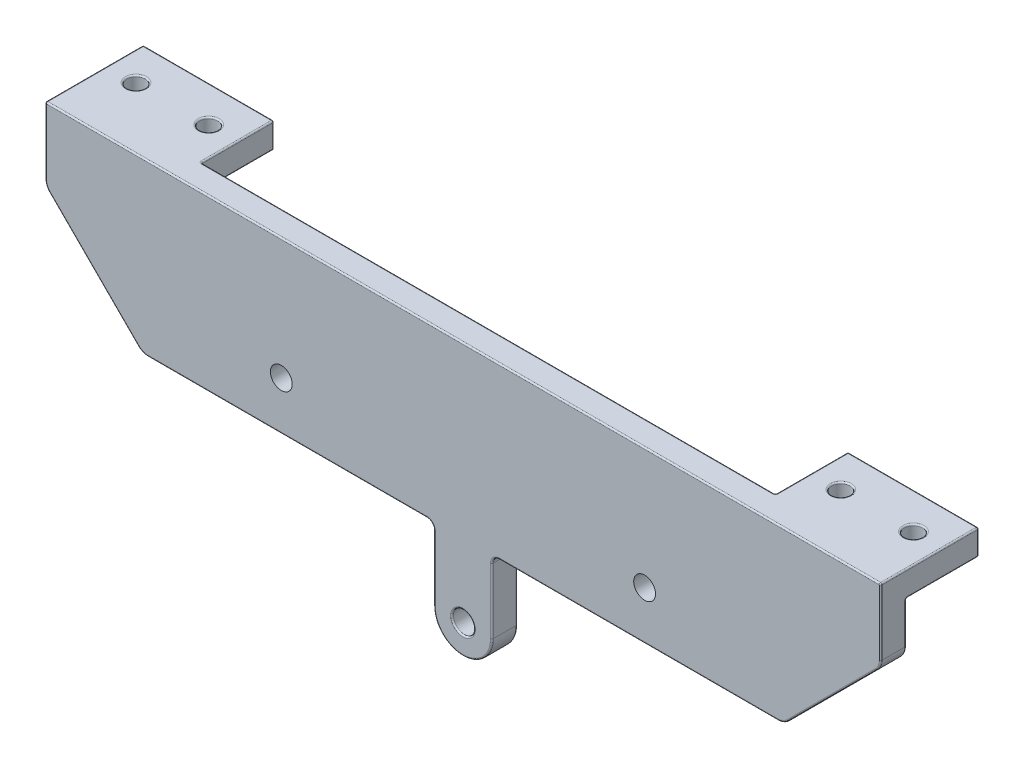
SolidWorks part; units mm, degrees
ref_plane "Front Plane" through (0, 0, 0) normal (0, 0, 1) x (1, 0, 0)
ref_plane "Top Plane" through (0, 0, 0) normal (0, 1, 0) x (1, 0, 0)
ref_plane "Right Plane" through (0, 0, 0) normal (1, 0, 0) x (0, 0, -1)
sketch "Sketch1" plane through (0, 0, 0) normal (0, 0, 1) x (1, 0, 0)
  line L0 (-300, 0) -> (300, 0) construction
  line L1 (-300, 0) -> (0, 300) construction
  line L2 (0, 300) -> (300, 0) construction
  line L3 (-150, 150) -> (0, 0) construction
  line L4 (0, 300) -> (0, 180) construction
  line L5 (-120, 180) -> (120, 180) construction
  circle A0 centre (-300, 0) radius 60
  circle A1 centre (0, 0) radius 60
  circle A2 centre (300, 0) radius 60
  point P3 (0, 0)
  dimension "D3" = 120
  dimension "D1" = 600
  dimension "D2" = 90
  dimension "D4" = 240
sketch "Sketch2" plane through (0, 0, 0) normal (0, 0, 1) x (1, 0, 0)
  line L0 (-169.5495, 130.4505) -> (-120, 180) construction
  line L1 (-300, 0) -> (0, 300) construction
  line L2 (-120, 180) -> (120, 180) construction
  line L3 (120, 180) -> (259.6949, 40.3051) construction
  line L4 (0, 300) -> (300, 0) construction
  line L5 (-148.3363, 109.2373) -> (-107.5736, 150)
  line L6 (-107.5736, 150) -> (107.5736, 150)
  line L7 (107.5736, 150) -> (238.4817, 19.0919)
  line L8 (-190.7627, 151.6637) -> (-132.4264, 210)
  line L9 (-132.4264, 210) -> (132.4264, 210)
  line L10 (132.4264, 210) -> (280.9081, 61.5183)
  line L11 (-190.7627, 151.6637) -> (-148.3363, 109.2373)
  line L12 (280.9081, 61.5183) -> (238.4817, 19.0919)
  line L13 (270.3015, 50.9117) -> (310.6066, 10.6066)
  line L14 (249.0883, 29.6985) -> (289.3934, -10.6066)
  line L15 (270.3015, 72.1249) -> (227.8751, 29.6985) construction
  line L16 (0, 300) -> (0, 180) construction
  line L17 (7.3072, 256.2398) -> (18, 210)
  line L18 (-7.3072, 256.2398) -> (-18, 210)
  circle A0 centre (300, 0) radius 10.5
  arc A1 (289.3934, -10.6066) -> (310.6066, 10.6066) centre (300, 0) ccw
  circle A2 centre (300, 0) radius 30 construction
  circle A3 centre (238.4817, 40.3051) radius 3
  circle A4 centre (259.6949, 61.5183) radius 3
  circle A5 centre (0, 180) radius 4.5
  circle A6 centre (0, 254.55) radius 4.5
  arc A7 (7.3072, 256.2398) -> (-7.3072, 256.2398) centre (0, 254.55) ccw
  circle A8 centre (-150, 150) radius 4.5
  dimension "D4" = 21
  dimension "D5" = 30
  dimension "D6" = 60
  dimension "6" = 6
  dimension "D12" = 9
  dimension "D13" = 44.55
  dimension "D14" = 15
  dimension "D17" = 9
  dimension "D1" = 30
  dimension "D3" = 82.5
  dimension "D7" = 57
  dimension "D8" = 15
  dimension "D10" = 15
  dimension "D11" = 15
  dimension "D15" = 18
  dimension "D16" = 18
  dimension "D2" = 30
sketch "Sketch3" plane through (0, 0, 0) normal (0, 0, 1) x (1, 0, 0)
  line L0 (-259.6949, 40.3051) -> (-150, 150) construction
  line L1 (-300, 0) -> (0, 300) construction
  line L2 (-150, 150) -> (-40.3051, 40.3051) construction
  line L3 (-150, 150) -> (0, 0) construction
  line L4 (-238.4817, 19.0919) -> (-150, 107.5736)
  line L5 (-150, 107.5736) -> (-61.5183, 19.0919)
  line L6 (-280.9081, 61.5183) -> (-150, 192.4264)
  line L7 (-150, 192.4264) -> (-19.0919, 61.5183)
  line L8 (-238.4817, 19.0919) -> (-280.9081, 61.5183)
  line L9 (-61.5183, 19.0919) -> (-19.0919, 61.5183)
  line L10 (-270.3015, 50.9117) -> (-310.6066, 10.6066)
  line L11 (-249.0883, 29.6985) -> (-289.3934, -10.6066)
  line L12 (10.6066, 10.6066) -> (-29.6985, 50.9117)
  line L13 (-10.6066, -10.6066) -> (-50.9117, 29.6985)
  line L14 (-227.8751, 29.6985) -> (-270.3015, 72.1249) construction
  line L15 (-29.6985, 72.1249) -> (-72.1249, 29.6985) construction
  circle A0 centre (-300, 0) radius 30 construction
  circle A1 centre (-300, 0) radius 10.5
  arc A2 (-310.6066, 10.6066) -> (-289.3934, -10.6066) centre (-300, 0) ccw
  circle A3 centre (0, 0) radius 30 construction
  arc A4 (-10.6066, -10.6066) -> (10.6066, 10.6066) centre (0, 0) ccw
  circle A5 centre (0, 0) radius 10.5
  circle A6 centre (-238.4817, 40.3051) radius 3
  circle A7 centre (-259.6949, 61.5183) radius 3
  circle A8 centre (-61.5183, 40.3051) radius 3
  circle A9 centre (-40.3051, 61.5183) radius 3
  circle A10 centre (-150, 150) radius 4.5 construction
  circle A11 centre (-150, 150) radius 4.5
  dimension "D1" = 60
  dimension "D2" = 21
  dimension "D3" = 30
  dimension "D4" = 30
  dimension "D9" = 6
  dimension "D13" = 6
  dimension "D14" = 15
  dimension "D6" = 57
  dimension "D7" = 57
  dimension "D8" = 15
  dimension "D10" = 15
  dimension "D11" = 15
  dimension "D12" = 15
  dimension "D15" = 15
  dimension "D5" = 30
sketch "Sketch4" plane through (0, 0, 0) normal (0, 0, 1) x (1, 0, 0)
  line L0 (-172.5, 280.0736) -> (172.5, 280.0736)
  line L1 (-172.5, 280.0736) -> (-172.5, 250.0736)
  line L2 (-172.5, 250.0736) -> (-132.4264, 210)
  line L3 (-132.4264, 210) -> (132.4264, 210)
  line L4 (132.4264, 210) -> (172.5, 250.0736)
  line L5 (172.5, 250.0736) -> (172.5, 280.0736)
  line L6 (12, 180) -> (12, 210)
  line L7 (-12, 180) -> (-12, 210)
  line L8 (-67.5, 254.5736) -> (67.5, 254.5736) construction
  line L9 (-67.5, 268.0736) -> (67.5, 268.0736)
  line L10 (-67.5, 241.0736) -> (67.5, 241.0736)
  line L12 (0, 300) -> (0, 180) construction
  circle A0 centre (0, 180) radius 4.5 construction
  circle A1 centre (0, 180) radius 4.5
  arc A2 (-12, 180) -> (12, 180) centre (0, 180) ccw
  circle A3 centre (0, 180) radius 12 construction
  arc A4 (-67.5, 268.0736) -> (-67.5, 241.0736) centre (-67.5, 254.5736) ccw
  arc A5 (67.5, 241.0736) -> (67.5, 268.0736) centre (67.5, 254.5736) ccw
  point P2 (0, 280.0736)
  point P21 (0, 254.5736)
  dimension "D1" = 345
  dimension "D2" = 30
  dimension "D3" = 135
  dimension "D5" = 135
  dimension "D6" = 27
  dimension "D7" = 12
  dimension "D4" = 7.5
sketch "Sketch5" plane through (0, 0, 0) normal (0, 0, 1) x (1, 0, 0)
  line L0 (12, 180) -> (12, 210) construction
  line L1 (-12, 180) -> (-12, 210) construction
  line L6 (172.5, 280.0736) -> (-172.5, 280.0736)
  line L7 (172.5, 250.0736) -> (172.5, 280.0736)
  line L8 (132.4264, 210) -> (172.5, 250.0736)
  line L9 (-132.4264, 210) -> (132.4264, 210)
  line L10 (-172.5, 250.0736) -> (-132.4264, 210)
  line L11 (-172.5, 280.0736) -> (-172.5, 250.0736)
  line L12 (172.5, 280.0736) -> (-172.5, 280.0736)
  line L13 (172.5, 250.0736) -> (172.5, 280.0736)
  line L14 (132.4264, 210) -> (172.5, 250.0736)
  line L15 (-132.4264, 210) -> (-12, 210)
  line L16 (-172.5, 250.0736) -> (-132.4264, 210)
  line L17 (-172.5, 280.0736) -> (-172.5, 250.0736)
  line L18 (12, 180) -> (12, 210)
  line L19 (-12, 180) -> (-12, 210)
  line L20 (12, 210) -> (132.4264, 210)
  arc A0 (-12, 180) -> (12, 180) centre (0, 180) ccw construction
  circle A1 centre (0, 180) radius 4.5
  circle A2 centre (0, 180) radius 4.5
  arc A3 (-12, 180) -> (12, 180) centre (0, 180) ccw
  dimension "D1" = 0
  dimension "D2" = 0
extrude "Boss-Extrude2" add sketch "Sketch5" along normal blind 10.5
sketch "Sketch8" plane through (0, 280.0736, 0) normal (0, 1, 0) x (1, 0, 0)
  line L0 (-172.5, 0) -> (-118.5, 0)
  line L1 (172.5, 0) -> (-172.5, 0) construction
  line L2 (-118.5, 0) -> (-118.5, 30)
  line L3 (-118.5, 30) -> (-172.5, 30)
  line L4 (-172.5, 30) -> (-172.5, 0)
  line L5 (-118.5, 15) -> (-172.5, 15) construction
  line L6 (-145.5, 30) -> (-145.5, 15) construction
  line L7 (0, 0) -> (0, 31.184) construction
  line L8 (145.5, 30) -> (145.5, 15) construction
  line L9 (118.5, 15) -> (172.5, 15) construction
  line L10 (172.5, 30) -> (172.5, 0)
  line L11 (118.5, 30) -> (172.5, 30)
  line L12 (118.5, 0) -> (118.5, 30)
  line L13 (172.5, 0) -> (118.5, 0)
  circle A0 centre (-130.5, 15) radius 3.75
  circle A1 centre (-160.5, 15) radius 3.75
  circle A2 centre (160.5, 15) radius 3.75
  circle A3 centre (130.5, 15) radius 3.75
  dimension "D3" = 30
  dimension "D4" = 7.5
  dimension "D1" = 54
  dimension "D2" = 30
extrude "Boss-Extrude3" add sketch "Sketch8" against normal blind 10.5
fillet "Fillet1" radius 6 4 edges at (172.5, 250.0736, 5.25) (132.4264, 210, 5.25) (-172.5, 250.0736, 5.25) (-132.4264, 210, 5.25)
fillet "Fillet3" radius 3 2 edges at (12, 210, 5.25) (-12, 210, 5.25)
fillet "Fillet5" radius 0.6 62 edges at (172.5, 274.8236, -30) (118.5, 274.8236, 0) (118.5, 274.8236, -30) (172.5, 269.5736, -15) (145.5, 269.5736, 0) (118.5, 269.5736, -15) (145.5, 269.5736, -30) (118.5, 280.0736, -15) (145.5, 280.0736, -30) (160.5, 269.5736, -18.75) (160.5, 280.0736, -18.75) (130.5, 269.5736, -18.75) (130.5, 280.0736, -18.75) (-160.5, 280.0736, -11.25) (-160.5, 269.5736, -11.25) (-130.5, 280.0736, -11.25) (-130.5, 269.5736, -11.25) (-118.5, 280.0736, -15) (-118.5, 269.5736, -15) (-145.5, 280.0736, -30) (-145.5, 269.5736, -30) (-172.5, 269.5736, -15) (-145.5, 269.5736, 0) (-118.5, 274.8236, 0) (-118.5, 274.8236, -30) (-172.5, 274.8236, -30) (4.5, 180, 0) (4.5, 180, 10.5) (-172.5, 261.0662, 0) (-152.4632, 230.0368, 0) (-72.4706, 210, 0) (-12, 193.5, 0) (0, 168, 0) (12, 193.5, 0) (72.4706, 210, 0) (152.4632, 230.0368, 0) (172.5, 261.0662, 0) (0, 280.0736, 0) (-172.5, 266.3162, 10.5) (-152.4632, 230.0368, 10.5) (-72.4706, 210, 10.5) (-12, 193.5, 10.5) (0, 168, 10.5) (12, 193.5, 10.5) (72.4706, 210, 10.5) (152.4632, 230.0368, 10.5) (172.5, 266.3162, 10.5) (0, 280.0736, 10.5) (-172.5, 280.0736, -9.75) (172.5, 280.0736, -9.75) (-132.2372, 210.4567, 0) (-172.0433, 250.2628, 0) (132.2372, 210.4567, 0) (172.0433, 250.2628, 0) (-132.2372, 210.4567, 10.5) (-172.0433, 250.2628, 10.5) (132.2372, 210.4567, 10.5) (172.0433, 250.2628, 10.5) (12.8787, 209.1213, 0) (12.8787, 209.1213, 10.5) (-12.8787, 209.1213, 0) (-12.8787, 209.1213, 10.5)
sketch "Sketch11" plane through (0, 0, 10.5) normal (0, 0, 1) x (1, 0, 0)
  line L0 (0, 180) -> (0, 280.0736) construction
  line L1 (-171.9, 280.0736) -> (171.9, 280.0736) construction
  circle A0 centre (75, 230) radius 4.5
  circle A1 centre (0, 180) radius 5.1 construction
  circle A2 centre (-75, 230) radius 4.5
  dimension "D1" = 9
  dimension "D2" = 75
  dimension "D3" = 50
extrude "Cut-Extrude3" cut sketch "Sketch11" against normal through all
scale "Scale1" scale about centroid uniform scaling yes scale factor 0.5
